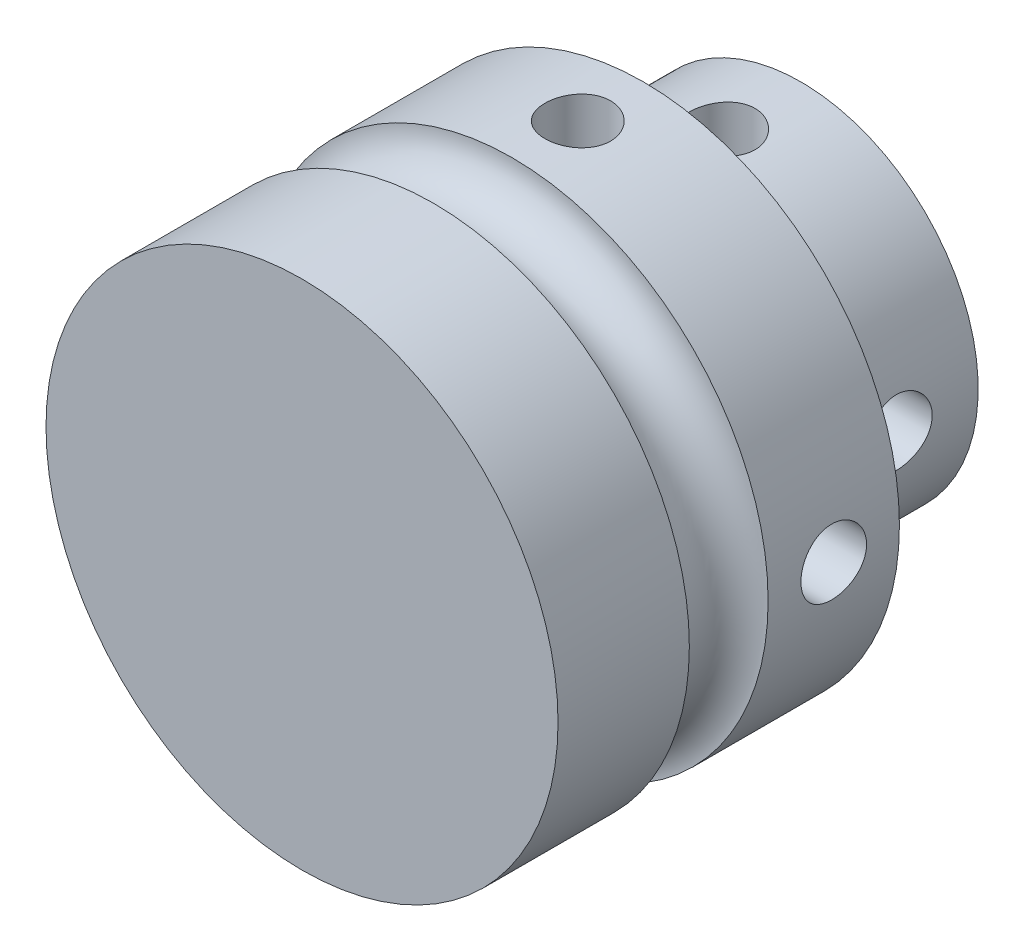
SolidWorks part; units mm, degrees
ref_plane "Plano frontal" through (0, 0, 0) normal (0, 0, 1) x (1, 0, 0)
ref_plane "Plano superior" through (0, 0, 0) normal (0, 1, 0) x (1, 0, 0)
ref_plane "Plano direito" through (0, 0, 0) normal (1, 0, 0) x (0, 0, -1)
sketch "Esboço2" plane through (0, 0, 0) normal (0, 0, 1) x (1, 0, 0)
  circle A0 centre (0, 0) radius 9.75
  dimension "D1" = 19.5
extrude "Ressalto-extrusão1" add sketch "Esboço2" along normal blind 13 contours A0
sketch "Esboço3" plane through (0, 0, 0) normal (0, 1, 0) x (1, 0, 0)
  line L0 (-9.75, -6.5) -> (9.75, -6.5) construction
  line L1 (-9.75, 0) -> (-9.75, -13) construction
  line L2 (9.75, -13) -> (9.75, 0) construction
  line L3 (0, 0) -> (0, -13) construction
  line L4 (-9.75, -13) -> (9.75, -13) construction
  circle A0 centre (9.75, -6.5) radius 1.5
  dimension "D1" = 3
revolve "Corte-Revolução1" cut sketch "Esboço3" angle 360 about L3
sketch "Esboço4" plane through (0, 0, 0) normal (0, 0, -1) x (-1, 0, 0)
  circle A0 centre (0, 0) radius 6.75
  dimension "D1" = 13.5
extrude "Ressalto-extrusão2" add sketch "Esboço4" along normal blind 6
sketch "Esboço11" plane through (0, 0, 0) normal (0, 1, 0) x (1, 0, 0)
  line L0 (0, 0) -> (0, -5) construction
  line L1 (9.75, -5) -> (-9.75, -5) construction
  circle A0 centre (0, -2.5) radius 1.5
  dimension "D1" = 3
ref_plane "Plano1" through (0, 9.75, 0) normal (0, 1, 0) x (1, 0, 0)
sketch "Esboço12" plane through (0, 9.75, 0) normal (0, 1, 0) x (1, 0, 0)
  point P0 (0, -2.5)
  point P1 (0, 0)
  point P3 (0, 0)
  point P4 (0, 0)
  point P5 (0, 0)
hole_wizard "Broca de rosquear para tarraxa de M36" positions "Esboço14" profile "Esboço15" hole size "M3" standard "ISO"
sketch "Esboço14" plane through (0, 9.75, 0) normal (0, 1, 0) x (1, 0, 0)
  point P0 (0, -2.5)
sketch "Esboço15" plane through (0, 9.75, 2.5) normal (1, 0, 0) x (0, 0, 1)
  line L0 (0, 0) -> (0, 8.7511)
  line L1 (0, 8.7511) -> (1.25, 8)
  line L2 (1.25, 8) -> (1.25, 0)
  line L5 (1.25, 0) -> (0, 0)
  line L10 (0, 8.7511) -> (-1.25, 8) construction
  line L11 (0, -6.35) -> (0, 107.95) construction
  dimension "Hole Dia." = 2.5
  dimension "Hole Depth" = 8
  dimension "Drill Angle" = 118
pattern_circular "PadrãoCircular1" count 4 over 360 about axis through (0, 0, 0) along (0, 0, 1) of "Broca de rosquear para tarraxa de M36"
ref_plane "Plano2" through (0, 6.75, 0) normal (0, 1, 0) x (1, 0, 0)
sketch "Esboço16" plane through (0, 6.75, 0) normal (0, 1, 0) x (1, 0, 0)
  line L0 (0, 6) -> (0, 0) construction
  line L1 (6.75, 6) -> (-6.75, 6) construction
  point P5 (0, 3)
hole_wizard "Broca de rosquear para tarraxa de M310" positions "Esboço18" profile "Esboço19" hole size "M3" standard "ISO"
sketch "Esboço18" plane through (0, 6.75, 0) normal (0, 1, 0) x (1, 0, 0)
  point P0 (0, 3)
sketch "Esboço19" plane through (0, 6.75, -3) normal (1, 0, 0) x (0, 0, 1)
  line L0 (0, 0) -> (0, 5.7511)
  line L1 (0, 5.7511) -> (1.25, 5)
  line L2 (1.25, 5) -> (1.25, 0)
  line L5 (1.25, 0) -> (0, 0)
  line L10 (0, 5.7511) -> (-1.25, 5) construction
  line L11 (0, -6.35) -> (0, 107.95) construction
  dimension "Hole Dia." = 2.5
  dimension "Hole Depth" = 5
  dimension "Drill Angle" = 118
pattern_circular "PadrãoCircular2" count 4 over 360 about axis through (0, 0, 0) along (0, 0, 1) of "Broca de rosquear para tarraxa de M310"
